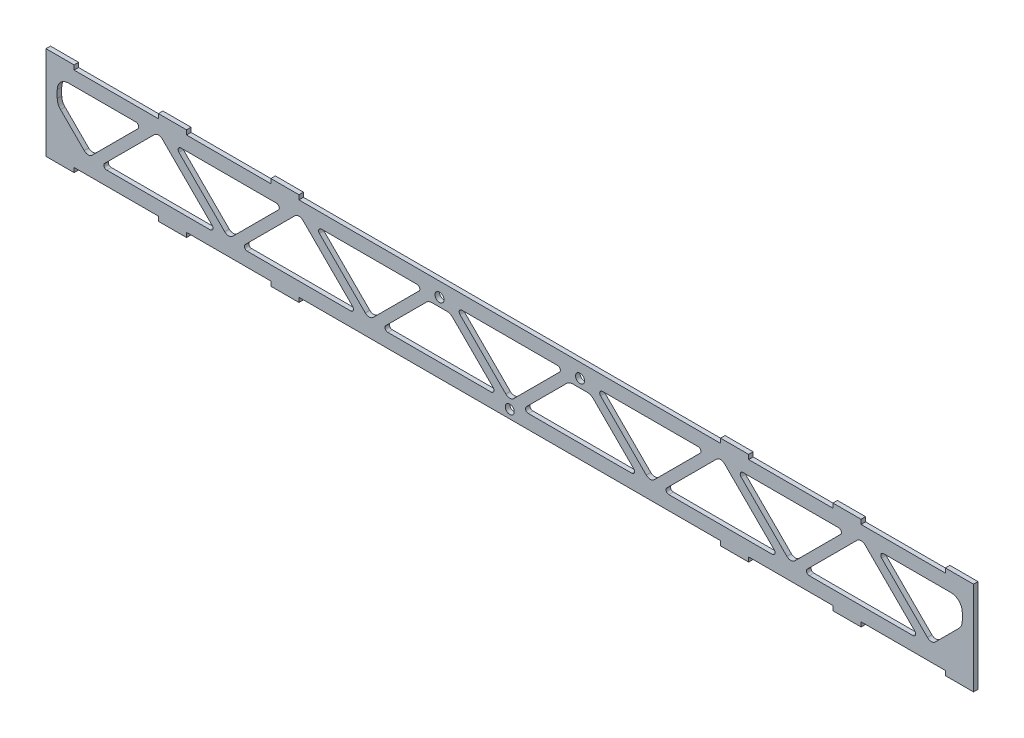
SolidWorks part; units mm, degrees
ref_plane "Front Plane" through (0, 0, 0) normal (0, 0, 1) x (1, 0, 0)
ref_plane "Top Plane" through (0, 0, 0) normal (0, 1, 0) x (1, 0, 0)
ref_plane "Right Plane" through (0, 0, 0) normal (1, 0, 0) x (0, 0, -1)
sketch "Sketch1" plane through (0, 0, 0) normal (0, 0, 1) x (1, 0, 0)
  line L1 (-180, -15) -> (180, -15)
  line L2 (-180, -15) -> (-180, 15)
  line L3 (-180, 15) -> (180, 15)
  line L4 (180, -15) -> (180, 15)
  line L5 (-180, -15) -> (180, 15) construction
  line L6 (-180, 15) -> (180, -15) construction
  point P0 (0, 0)
  dimension "D1" = 360
  dimension "D2" = 30
extrude "Boss-Extrude1" add sketch "Sketch1" along normal blind 1.6
sketch "Sketch2" plane through (0, 0, 1.6) normal (0, 0, 1) x (1, 0, 0)
  line L0 (0, 15) -> (0, -15) construction
  line L1 (180, 15) -> (-180, 15) construction
  line L2 (-180, -15) -> (180, -15) construction
  line L3 (115, 15) -> (125, 15)
  line L4 (75, 15) -> (85, 15)
  line L5 (75, 15) -> (75, 16.6)
  line L6 (75, 16.6) -> (85, 16.6)
  line L7 (85, 15) -> (85, 16.6)
  line L8 (115, 15) -> (115, 16.6)
  line L9 (115, 16.6) -> (125, 16.6)
  line L10 (125, 15) -> (125, 16.6)
  line L11 (155, 15) -> (165, 15)
  line L12 (155, 15) -> (155, 16.6)
  line L13 (155, 16.6) -> (165, 16.6)
  line L14 (165, 15) -> (165, 16.6)
  line L15 (-165, 15) -> (-165, 16.6)
  line L16 (-155, 16.6) -> (-165, 16.6)
  line L17 (-155, 15) -> (-155, 16.6)
  line L18 (-155, 15) -> (-165, 15)
  line L19 (-125, 15) -> (-125, 16.6)
  line L20 (-115, 16.6) -> (-125, 16.6)
  line L21 (-115, 15) -> (-115, 16.6)
  line L22 (-85, 15) -> (-85, 16.6)
  line L23 (-75, 16.6) -> (-85, 16.6)
  line L24 (-75, 15) -> (-75, 16.6)
  line L25 (-75, 15) -> (-85, 15)
  line L26 (-115, 15) -> (-125, 15)
  line L27 (-180, 0) -> (180, 0) construction
  line L28 (-180, 15) -> (-180, -15) construction
  line L29 (180, -15) -> (180, 15) construction
  line L30 (-115, -15) -> (-125, -15)
  line L31 (-75, -15) -> (-85, -15)
  line L32 (-75, -15) -> (-75, -16.6)
  line L33 (-75, -16.6) -> (-85, -16.6)
  line L34 (-85, -15) -> (-85, -16.6)
  line L35 (-115, -15) -> (-115, -16.6)
  line L36 (-115, -16.6) -> (-125, -16.6)
  line L37 (-125, -15) -> (-125, -16.6)
  line L38 (-155, -15) -> (-165, -15)
  line L39 (-155, -15) -> (-155, -16.6)
  line L40 (-155, -16.6) -> (-165, -16.6)
  line L41 (-165, -15) -> (-165, -16.6)
  line L42 (165, -15) -> (165, -16.6)
  line L43 (155, -16.6) -> (165, -16.6)
  line L44 (155, -15) -> (155, -16.6)
  line L45 (155, -15) -> (165, -15)
  line L46 (125, -15) -> (125, -16.6)
  line L47 (115, -16.6) -> (125, -16.6)
  line L48 (115, -15) -> (115, -16.6)
  line L49 (85, -15) -> (85, -16.6)
  line L50 (75, -16.6) -> (85, -16.6)
  line L51 (75, -15) -> (75, -16.6)
  line L52 (75, -15) -> (85, -15)
  line L53 (115, -15) -> (125, -15)
  dimension "D1" = 10
  dimension "D2" = 75
  dimension "D3" = 1.6
  dimension "D5" = 30
  dimension "D4" = 3
extrude "Boss-Extrude2" add sketch "Sketch2" against normal up to surface (1.6 mm away) up to face at (0, 0, 0)
sketch "Sketch3" plane through (0, 0, 1.6) normal (0, 0, 1) x (1, 0, 0)
  line L0 (-167, 10) -> (-133, 10)
  line L1 (-167.7071, 8.2929) -> (-151.4142, -8)
  line L3 (-180, 15) -> (-180, -15) construction
  line L4 (-150, -10) -> (-150, 10) construction
  line L5 (-125, 15) -> (-155, 15) construction
  line L6 (-132.2929, 8.2929) -> (-148.5858, -8)
  line L7 (-117, 10) -> (-83, 10)
  line L8 (-117.7071, 8.2929) -> (-101.4142, -8)
  line L9 (-82.2929, 8.2929) -> (-98.5858, -8)
  line L10 (-100, -10) -> (-100, 10) construction
  line L11 (-67, 10) -> (-33, 10)
  line L12 (-67.7071, 8.2929) -> (-51.4142, -8)
  line L13 (-32.2929, 8.2929) -> (-48.5858, -8)
  line L14 (-50, -10) -> (-50, 10) construction
  line L15 (-17, 10) -> (17, 10)
  line L16 (-17.7071, 8.2929) -> (-1.4142, -8)
  line L17 (17.7071, 8.2929) -> (1.4142, -8)
  line L18 (0, -10) -> (0, 10) construction
  line L19 (33, 10) -> (67, 10)
  line L20 (32.2929, 8.2929) -> (48.5858, -8)
  line L21 (67.7071, 8.2929) -> (51.4142, -8)
  line L22 (50, -10) -> (50, 10) construction
  line L23 (83, 10) -> (117, 10)
  line L24 (82.2929, 8.2929) -> (98.5858, -8)
  line L25 (117.7071, 8.2929) -> (101.4142, -8)
  line L26 (100, -10) -> (100, 10) construction
  line L27 (133, 10) -> (167, 10)
  line L28 (132.2929, 8.2929) -> (148.5858, -8)
  line L29 (167.7071, 8.2929) -> (151.4142, -8)
  line L30 (150, -10) -> (150, 10) construction
  arc A0 (-167, 10) -> (-167.7071, 8.2929) centre (-167, 9) ccw
  arc A1 (-151.4142, -8) -> (-148.5858, -8) centre (-150, -6.5858) ccw
  arc A2 (-133, 10) -> (-132.2929, 8.2929) centre (-133, 9) cw
  arc A3 (-117, 10) -> (-117.7071, 8.2929) centre (-117, 9) ccw
  arc A4 (-101.4142, -8) -> (-98.5858, -8) centre (-100, -6.5858) ccw
  arc A5 (-83, 10) -> (-82.2929, 8.2929) centre (-83, 9) cw
  arc A6 (-67, 10) -> (-67.7071, 8.2929) centre (-67, 9) ccw
  arc A7 (-51.4142, -8) -> (-48.5858, -8) centre (-50, -6.5858) ccw
  arc A8 (-33, 10) -> (-32.2929, 8.2929) centre (-33, 9) cw
  arc A9 (-17, 10) -> (-17.7071, 8.2929) centre (-17, 9) ccw
  arc A10 (-1.4142, -8) -> (1.4142, -8) centre (0, -6.5858) ccw
  arc A11 (17, 10) -> (17.7071, 8.2929) centre (17, 9) cw
  arc A12 (33, 10) -> (32.2929, 8.2929) centre (33, 9) ccw
  arc A13 (48.5858, -8) -> (51.4142, -8) centre (50, -6.5858) ccw
  arc A14 (67, 10) -> (67.7071, 8.2929) centre (67, 9) cw
  arc A15 (83, 10) -> (82.2929, 8.2929) centre (83, 9) ccw
  arc A16 (98.5858, -8) -> (101.4142, -8) centre (100, -6.5858) ccw
  arc A17 (117, 10) -> (117.7071, 8.2929) centre (117, 9) cw
  arc A18 (133, 10) -> (132.2929, 8.2929) centre (133, 9) ccw
  arc A19 (148.5858, -8) -> (151.4142, -8) centre (150, -6.5858) ccw
  arc A20 (167, 10) -> (167.7071, 8.2929) centre (167, 9) cw
  point P2 (-150, 0)
  point P9 (-180, 0)
  point P20 (-100, 0)
  point P34 (-50, 0)
  point P46 (0, 0)
  point P58 (50, 0)
  point P70 (100, 0)
  point P82 (150, 0)
  dimension "D3" = 1
  dimension "D7" = 2
  dimension "D1" = 5
  dimension "D2" = 45
  dimension "D4" = 30
  dimension "D5" = 7
  dimension "D6" = 50
  dimension "D8" = 34
extrude "Cut-Extrude1" cut sketch "Sketch3" against normal through all
sketch "Sketch4" plane through (0, 0, 1.6) normal (0, 0, 1) x (1, 0, 0)
  line L0 (-125, 10) -> (-125, -10) construction
  line L1 (-167, 10) -> (-133, 10) construction
  line L2 (-150, -10) -> (-150, 10) construction
  line L6 (-180, 0) -> (180, 0) construction
  line L7 (180, -15) -> (180, 15) construction
  line L8 (-143.4142, -10) -> (-106.5858, -10)
  line L9 (-105.8787, -8.2929) -> (-123.5858, 9.4142)
  line L10 (-144.1213, -8.2929) -> (-126.4142, 9.4142)
  line L11 (-155, -15) -> (-125, -15) construction
  line L12 (-93.4142, -10) -> (-56.5858, -10)
  line L13 (-55.8787, -8.2929) -> (-73.5858, 9.4142)
  line L14 (-94.1213, -8.2929) -> (-76.4142, 9.4142)
  line L15 (-75, 10) -> (-75, -10) construction
  line L16 (-43.4142, -10) -> (-6.5858, -10)
  line L17 (-5.8787, -8.2929) -> (-23.5858, 9.4142)
  line L18 (-44.1213, -8.2929) -> (-26.4142, 9.4142)
  line L19 (-25, 10) -> (-25, -10) construction
  line L20 (6.5858, -10) -> (43.4142, -10)
  line L21 (44.1213, -8.2929) -> (26.4142, 9.4142)
  line L22 (5.8787, -8.2929) -> (23.5858, 9.4142)
  line L23 (25, 10) -> (25, -10) construction
  line L24 (56.5858, -10) -> (93.4142, -10)
  line L25 (94.1213, -8.2929) -> (76.4142, 9.4142)
  line L26 (55.8787, -8.2929) -> (73.5858, 9.4142)
  line L27 (75, 10) -> (75, -10) construction
  line L28 (106.5858, -10) -> (143.4142, -10)
  line L29 (144.1213, -8.2929) -> (126.4142, 9.4142)
  line L30 (105.8787, -8.2929) -> (123.5858, 9.4142)
  line L31 (125, 10) -> (125, -10) construction
  arc A0 (-76.4142, 9.4142) -> (-73.5858, 9.4142) centre (-75, 8) cw
  arc A1 (-55.8787, -8.2929) -> (-56.5858, -10) centre (-56.5858, -9) cw
  arc A4 (-93.4142, -10) -> (-94.1213, -8.2929) centre (-93.4142, -9) cw
  arc A6 (-126.4142, 9.4142) -> (-123.5858, 9.4142) centre (-125, 8) cw
  arc A7 (-105.8787, -8.2929) -> (-106.5858, -10) centre (-106.5858, -9) cw
  arc A8 (-143.4142, -10) -> (-144.1213, -8.2929) centre (-143.4142, -9) cw
  arc A9 (-26.4142, 9.4142) -> (-23.5858, 9.4142) centre (-25, 8) cw
  arc A10 (-5.8787, -8.2929) -> (-6.5858, -10) centre (-6.5858, -9) cw
  arc A11 (-43.4142, -10) -> (-44.1213, -8.2929) centre (-43.4142, -9) cw
  arc A12 (23.5858, 9.4142) -> (26.4142, 9.4142) centre (25, 8) cw
  arc A13 (44.1213, -8.2929) -> (43.4142, -10) centre (43.4142, -9) cw
  arc A14 (6.5858, -10) -> (5.8787, -8.2929) centre (6.5858, -9) cw
  arc A15 (73.5858, 9.4142) -> (76.4142, 9.4142) centre (75, 8) cw
  arc A16 (94.1213, -8.2929) -> (93.4142, -10) centre (93.4142, -9) cw
  arc A17 (56.5858, -10) -> (55.8787, -8.2929) centre (56.5858, -9) cw
  arc A18 (123.5858, 9.4142) -> (126.4142, 9.4142) centre (125, 8) cw
  arc A19 (144.1213, -8.2929) -> (143.4142, -10) centre (143.4142, -9) cw
  arc A20 (106.5858, -10) -> (105.8787, -8.2929) centre (106.5858, -9) cw
  dimension "D1" = 1
  dimension "D3" = 2
  dimension "D2" = 45
  dimension "D4" = 25
  dimension "D5" = 5
  dimension "D7" = 50
  dimension "D6" = 6
extrude "Cut-Extrude2" cut sketch "Sketch4" against normal through all
sketch "Sketch5" plane through (0, 0, 1.6) normal (0, 0, 1) x (1, 0, 0)
  line L1 (-180, 15) -> (-165, 15)
  line L2 (-180, 15) -> (-180, -15)
  line L3 (-180, -15) -> (-165, -15)
  line L4 (-165, 15) -> (-165, -15)
  line L5 (165, 15) -> (180, 15)
  line L6 (165, 15) -> (165, -15)
  line L7 (165, -15) -> (180, -15)
  line L8 (180, 15) -> (180, -15)
extrude "Cut-Extrude3" cut sketch "Sketch5" against normal through all
sketch "Sketch6" plane through (0, 0, 1.6) normal (0, 0, 1) x (1, 0, 0)
  line L0 (-155, 16.6) -> (-165, 16.6) construction
  line L1 (-165, -16.6) -> (-161, -16.6)
  line L2 (-165, -16.6) -> (-165, 16.6)
  line L3 (-165, 16.6) -> (-161, 16.6)
  line L4 (-161, -16.6) -> (-161, 16.6)
  line L5 (0, 15) -> (0, -15) construction
  line L6 (75, 15) -> (-75, 15) construction
  line L7 (-75, -15) -> (75, -15) construction
  line L8 (161, -16.6) -> (161, 16.6)
  line L9 (165, 16.6) -> (161, 16.6)
  line L10 (165, -16.6) -> (165, 16.6)
  line L11 (165, -16.6) -> (161, -16.6)
  dimension "D1" = 4
extrude "Boss-Extrude3" add sketch "Sketch6" against normal up to surface (1.6 mm away) up to face at (0, 0.626, 0)
fillet "Fillet1" radius 4 4 edges at (161, 1.5858, 0.8) (161, 10, 0.8) (-161, 1.5858, 0.8) (-161, 10, 0.8)
sketch "Sketch7" plane through (0, 0, 1.6) normal (0, 0, 1) x (1, 0, 0)
  line L3 (0, 15) -> (0, -15) construction
  line L4 (75, 15) -> (-75, 15) construction
  line L5 (-75, -15) -> (75, -15) construction
  line L12 (-26.4142, 9.4142) -> (-44.1213, -8.2929) construction
  line L14 (-26.4142, 9.4142) -> (-29.7071, 6.1213)
  line L15 (-27.5858, 7) -> (-22.4142, 7)
  line L16 (-25, 10) -> (-25, 7) construction
  line L17 (-23.5858, 9.4142) -> (-20.2929, 6.1213)
  line L18 (25, 10) -> (25, 7) construction
  line L19 (23.5858, 9.4142) -> (20.2929, 6.1213)
  line L20 (27.5858, 7) -> (22.4142, 7)
  line L21 (26.4142, 9.4142) -> (29.7071, 6.1213)
  arc A0 (-23.5858, 9.4142) -> (-26.4142, 9.4142) centre (-25, 8) ccw construction
  arc A1 (-23.5858, 9.4142) -> (-26.4142, 9.4142) centre (-25, 8) ccw
  arc A2 (-29.7071, 6.1213) -> (-27.5858, 7) centre (-27.5858, 4) cw
  arc A3 (-20.2929, 6.1213) -> (-22.4142, 7) centre (-22.4142, 4) ccw
  arc A4 (20.2929, 6.1213) -> (22.4142, 7) centre (22.4142, 4) cw
  arc A5 (29.7071, 6.1213) -> (27.5858, 7) centre (27.5858, 4) ccw
  arc A6 (23.5858, 9.4142) -> (26.4142, 9.4142) centre (25, 8) cw
  dimension "D2" = 3
  dimension "D1" = 8
extrude "Boss-Extrude4" add sketch "Sketch7" against normal up to surface (1.6 mm away) up to face at (150.5826, 2.789, 0)
sketch "Sketch8" plane through (0, 0, 1.6) normal (0, 0, 1) x (1, 0, 0)
  line L0 (0, 15) -> (0, -15) construction
  line L1 (75, 15) -> (-75, 15) construction
  line L2 (-75, -15) -> (75, -15) construction
  line L4 (-27.5858, 7) -> (-22.4142, 7) construction
  circle A0 centre (-25, 10) radius 1.6
  circle A1 centre (25, 10) radius 1.6
  circle A2 centre (0, -12) radius 1.6
  point P17 (-25, 7)
  dimension "D1" = 3.2
  dimension "D2" = 5
  dimension "D3" = 3
extrude "Cut-Extrude4" cut sketch "Sketch8" against normal through all
